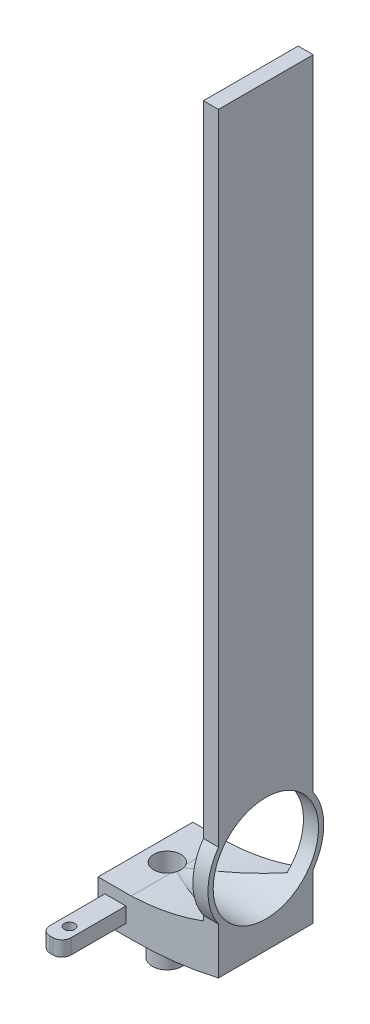
SolidWorks part; units mm, degrees
material "Cast Alloy Steel"
ref_plane "Front Plane" through (0, 0, 0) normal (0, 0, 1) x (1, 0, 0)
ref_plane "Top Plane" through (0, 0, 0) normal (0, 1, 0) x (1, 0, 0)
ref_plane "Right Plane" through (0, 0, 0) normal (1, 0, 0) x (0, 0, -1)
sketch "Sketch1" plane through (0, 0, 0) normal (0, 0, 1) x (1, 0, 0)
  line L0 (0, 0) -> (0, 25.0004)
  line L1 (0, 25.0004) -> (22, 25.0004)
  line L3 (22, 0) -> (0, 0)
  line L4 (0, 25.0004) -> (0, -234) construction
  line L8 (80, 38.7514) -> (80, 6.7987)
  arc A0 (22, 25.0004) -> (80, 38.7514) centre (15.9028, 179.9111) ccw
  arc A1 (22, 0) -> (80, 6.7987) centre (22, 250.8008) ccw
  dimension "D1" = 22
  dimension "D2" = 80
  dimension "D3" = 22
extrude "Boss-Extrude1" add sketch "Sketch1" along normal blind 48
sketch "Sketch2" plane through (0, 0, 48) normal (0, 0, 1) x (1, 0, 0)
  line L0 (0, 0) -> (0, 7.5) construction
  line L1 (0, 25.0004) -> (0, 0) construction
  line L2 (0, 7.5) -> (4.5, 7.5) construction
  line L3 (4.5, 7.5) -> (4.5, 17.5)
  line L4 (4.5, 17.5) -> (18.5, 17.5)
  line L5 (18.5, 17.5) -> (18.5, 7.5)
  line L6 (4.5, 7.5) -> (18.5, 7.5)
  dimension "D1" = 14
  dimension "D2" = 10
  dimension "D3" = 4.5
extrude "Boss-Extrude2" add sketch "Sketch2" along normal blind 50
ref_plane "Plane1" through (0, 0, 24) normal (0, 0, 1) x (1, 0, 0)
mirror "Mirror1" about plane through (0, 0, 24) normal (0, 0, 1) of "Boss-Extrude2"
sketch "Sketch3" plane through (0, 0, 0) normal (0, 1, 0) x (1, 0, 0)
  line L0 (11.5, 0) -> (11.5, 13.5)
  line L1 (18.5, 0) -> (4.5, 0) construction
  line L2 (11.5, 13.5) -> (-23.123, 13.5)
  line L3 (-23.123, 13.5) -> (-23.123, 84.8672)
  line L4 (-23.123, 84.8672) -> (32.759, 84.8672)
  line L5 (32.759, 84.8672) -> (32.759, 13.5)
  line L6 (32.759, 13.5) -> (11.5, 13.5)
extrude "Cut-Extrude1" cut sketch "Sketch3" along normal blind 98 contours L6 L5 L4 L3 L2
sketch "Sketch4" plane through (0, 17.5, 0) normal (0, 1, 0) x (1, 0, 0)
  line L0 (11.5, -48) -> (11.5, -86)
  line L1 (18.5, -48) -> (4.5, -48) construction
hole_wizard "M8x1.0 Tapped Hole1" positions "3DSketch1" profile "Sketch5" tap size "M8x1.0" standard "ANSI Metric"
sketch3d "3DSketch1"
  point P0 (11.5, 17.5, 86)
sketch "Sketch5" plane through (11.5, 17.5, 86) normal (1, 0, 0) x (0, 0, 1)
  line L0 (0, 0) -> (0, 12.103)
  line L1 (0, 12.103) -> (3.5, 10)
  line L2 (3.5, 10) -> (3.5, 0)
  line L5 (3.5, 0) -> (0, 0)
  line L10 (0, 12.103) -> (-3.5, 10) construction
  line L11 (0, -6.35) -> (0, 107.95) construction
  dimension "Tap Drill Dia." = 7
  dimension "Tap Drill Depth" = 10
  dimension "Drill Angle" = 118
cosmetic thread "Hole Thread1" parameters "D1"=10, "D2"=8
fillet "Fillet1" radius 6 2 edges at (4.5, 12.5, 98) (18.5, 12.5, 98)
ref_plane "Plane2" through (80, 0, 0) normal (-1, 0, 0) x (0, 0, 1)
sketch "Sketch7" plane through (80, 0, 0) normal (-1, 0, 0) x (0, 0, 1)
  line L0 (24, 25.0004) -> (24, 60.0004) construction
  line L1 (48, 25.0004) -> (0, 25.0004) construction
  circle A0 centre (24, 60.0004) radius 35
  circle A1 centre (24, 60.0004) radius 38.5
extrude "Boss-Extrude3" add sketch "Sketch7" along normal blind 10
sketch "Sketch8" plane through (80, 0, 0) normal (-1, 0, 0) x (0, 0, 1)
  circle A0 centre (24, 60.0004) radius 35
extrude "Cut-Extrude2" cut sketch "Sketch8" along normal blind 90
sketch "Sketch10" plane through (0, 0, 0) normal (0, -1, 0) x (1, 0, 0)
  line L0 (0, 24) -> (14.5, 24) construction
  line L1 (0, 48) -> (0, 0) construction
  circle A0 centre (14.5, 24) radius 12
  circle A1 centre (14.5, 24) radius 9
extrude "Boss-Extrude4" add sketch "Sketch10" along normal blind 5 and the other way blind 10
sketch "Sketch11" plane through (0, -5, 0) normal (0, -1, 0) x (1, 0, 0)
  circle A0 centre (14.5, 24) radius 10
  circle A1 centre (14.5, 24) radius 9
extrude "Boss-Extrude5" add sketch "Sketch11" along normal blind 25
sketch "Sketch12" plane through (0, 0, 0) normal (0, -1, 0) x (-1, 0, 0)
  circle A0 centre (-14.5, -24) radius 9
extrude "Cut-Extrude3" cut sketch "Sketch12" against normal blind 42
sketch "Sketch13" plane through (0, 0, 48) normal (0, 0, 1) x (1, 0, 0)
  line L0 (0, 25.0004) -> (0, 0)
  line L1 (0, 0) -> (22, 0)
  line L2 (0, 25.0004) -> (22, 25.0004)
  line L3 (69.7299, 34.5249) -> (70, 34.5249)
  line L6 (80, 29.8964) -> (80, 6.7987)
  line L10 (70, 34.5249) -> (80, 34.5249)
  line L11 (80, 29.8964) -> (80, 98.5004) construction
  line L12 (80, 34.5249) -> (80, 29.8964)
  arc A0 (22, 0) -> (80, 6.7987) centre (22, 250.8008) ccw construction
  arc A1 (22, 25.0004) -> (69.7299, 34.5249) centre (15.9028, 179.9111) ccw
  arc A2 (22, 0) -> (80, 6.7987) centre (22, 250.8008) ccw
extrude "Boss-Extrude6" add sketch "Sketch13" along normal blind 7.5
sketch "Sketch14" plane through (0, 0, 0) normal (0, 0, -1) x (-1, 0, 0)
  line L0 (-80, 29.8964) -> (-80, 6.7987)
  line L1 (-22, 0) -> (0, 0)
  line L2 (0, 0) -> (0, 25.0004)
  line L3 (0, 25.0004) -> (-22, 25.0004)
  line L4 (-69.7299, 34.5249) -> (-70, 34.5249)
  line L7 (-70, 34.5249) -> (-80, 34.5249)
  line L8 (-80, 98.5004) -> (-80, 29.8964) construction
  line L9 (-80, 34.5249) -> (-80, 29.8964)
  arc A0 (-80, 6.7987) -> (-22, 0) centre (-22, 250.8008) ccw
  arc A1 (-22, 25.0004) -> (-69.7299, 34.5249) centre (-15.9028, 179.9111) cw
extrude "Boss-Extrude7" add sketch "Sketch14" along normal blind 7.5
sketch "Sketch15" plane through (80, 0, 0) normal (1, 0, 0) x (0, 0, -1)
  line L0 (-55.5, 6.7987) -> (-55.5, 44.7443)
  line L1 (7.5, 6.7987) -> (7.5, 44.7443)
  line L2 (-55.5, 506.7987) -> (7.5, 506.7987)
  line L3 (-55.5, 6.7987) -> (7.5, 6.7987)
  line L4 (7.5, 75.2565) -> (7.5, 506.7987)
  line L5 (-55.5, 75.2565) -> (-55.5, 506.7987)
  arc A0 (-55.5, 75.2565) -> (7.5, 75.2565) centre (-24, 60.0004) cw
  circle A1 centre (-24, 60.0004) radius 35 construction
  arc A2 (-55.5, 44.7443) -> (7.5, 44.7443) centre (-24, 60.0004) ccw
extrude "Boss-Extrude8" add sketch "Sketch15" against normal up to surface (10 mm away) up to face at (70, 65.6377, 24)
